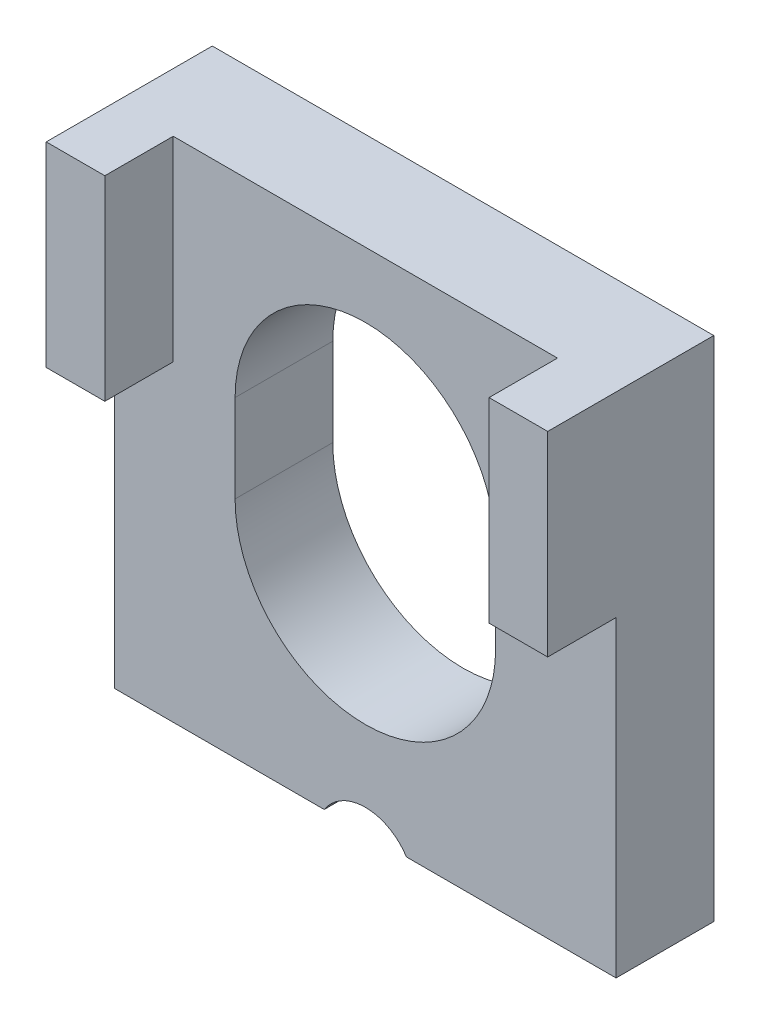
SolidWorks part; units mm, degrees
ref_plane "Спереди" through (0, 0, 0) normal (0, 0, 1) x (1, 0, 0)
ref_plane "Сверху" through (0, 0, 0) normal (0, 1, 0) x (1, 0, 0)
ref_plane "Справа" through (0, 0, 0) normal (1, 0, 0) x (0, 0, -1)
sketch "Эскиз1" plane through (0, 0, 0) normal (0, 0, 1) x (1, 0, 0)
  line L1 (-7.7, 13.7375) -> (7.7, 13.7375)
  line L5 (-7.7, 13.7375) -> (-7.7, -0.0396)
  line L6 (7.7, 13.7375) -> (7.7, -0.0396)
  line L7 (-7.7, -0.0396) -> (-7.7, -1.8492)
  line L8 (-7.7, -1.8492) -> (-1.2627, -1.8492)
  line L9 (0, 7.7375) -> (0, 5.041) construction
  line L10 (4, 7.7375) -> (4, 5.041)
  line L11 (-4, 7.7375) -> (-4, 5.041)
  line L12 (7.7, -0.0396) -> (7.7, -1.8492)
  line L13 (7.7, -1.8492) -> (1.2627, -1.8492)
  arc A0 (-1.2627, -1.8492) -> (1.2627, -1.8492) centre (0, -2.659) cw
  arc A1 (4, 7.7375) -> (-4, 7.7375) centre (0, 7.7375) ccw
  arc A2 (-4, 5.041) -> (4, 5.041) centre (0, 5.041) ccw
  point P1 (0, 6.3893)
  point P15 (0, 11.7375)
  point P16 (0, 1.041)
  dimension "D1" = 1.5
  dimension "D5" = 4
  dimension "D4" = 2.2
  dimension "D2" = 15.4
  dimension "D3" = 7.7
  dimension "D6" = 10.6965
  dimension "D7" = 2
  dimension "D8" = 7.7
extrude "Бобышка-Вытянуть1" add sketch "Эскиз1" along normal blind 3
sketch "Эскиз2" plane through (0, 0, 3) normal (0, 0, 1) x (1, 0, 0)
  line L1 (-7.7, 13.7375) -> (-5.9, 13.7375)
  line L2 (-7.7, 13.7375) -> (-7.7, 7.7375)
  line L3 (-7.7, 7.7375) -> (-5.9, 7.7375)
  line L4 (-5.9, 13.7375) -> (-5.9, 7.7375)
  line L5 (7.7, 13.7375) -> (5.9, 13.7375)
  line L6 (7.7, 13.7375) -> (7.7, 7.7375)
  line L7 (7.7, 7.7375) -> (5.9, 7.7375)
  line L8 (5.9, 13.7375) -> (5.9, 7.7375)
  dimension "D1" = 1.8
  dimension "D2" = 1.8
  dimension "D3" = 6
  dimension "D4" = 6
extrude "Бобышка-Вытянуть2" add sketch "Эскиз2" along normal blind 2.1
